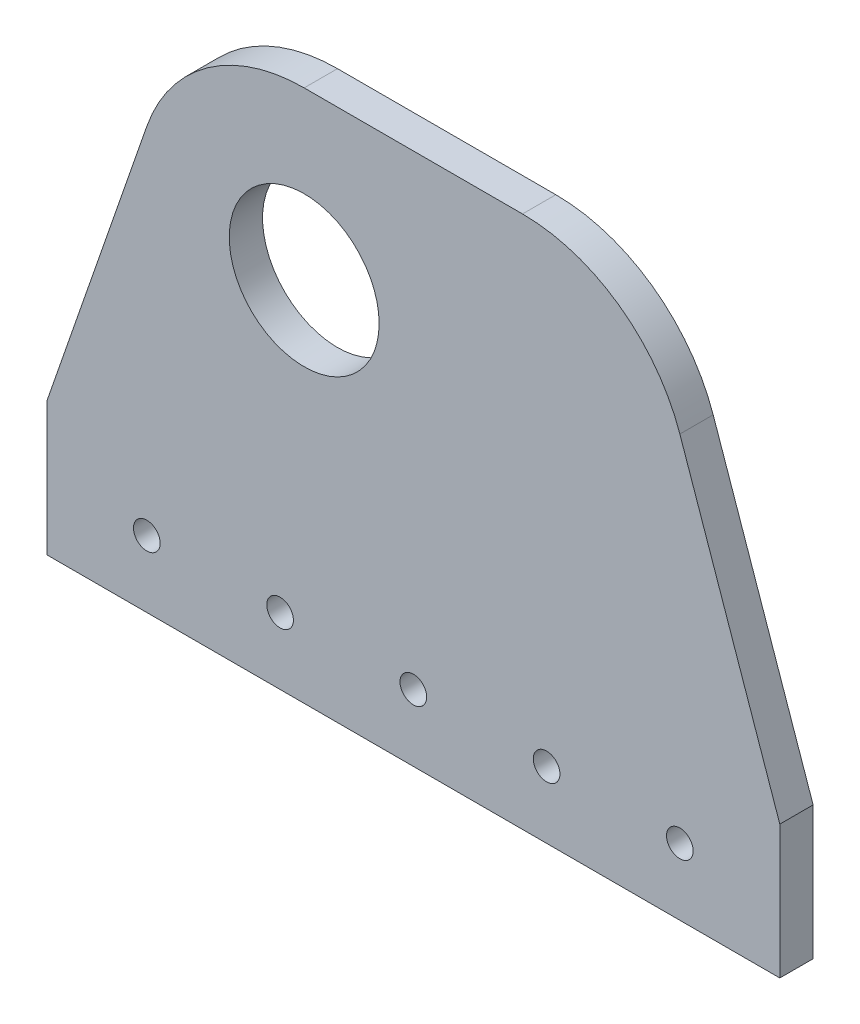
SolidWorks part; units mm, degrees
ref_plane "Front Plane" through (0, 0, 0) normal (0, 0, 1) x (1, 0, 0)
ref_plane "Top Plane" through (0, 0, 0) normal (0, 1, 0) x (1, 0, 0)
ref_plane "Right Plane" through (0, 0, 0) normal (1, 0, 0) x (0, 0, -1)
sketch "Sketch1" plane through (0, 0, 0) normal (0, 0, 1) x (1, 0, 0)
  line L1 (49.0434, 101.6) -> (90.6566, 101.6)
  line L2 (120.65, 80.2643) -> (139.7, 25.4)
  line L3 (139.7, 25.4) -> (139.7, 0)
  line L4 (139.7, 0) -> (0, 0)
  line L6 (0, 0) -> (0, 25.4)
  line L7 (0, 25.4) -> (19.05, 80.2643)
  line L8 (69.85, 0) -> (69.85, 101.6) construction
  arc A0 (49.0434, 101.6) -> (19.05, 80.2643) centre (49.0434, 69.85) ccw
  arc A1 (120.65, 80.2643) -> (90.6566, 101.6) centre (90.6566, 69.85) ccw
  circle A2 centre (49.0434, 69.85) radius 14.2875
  circle A3 centre (69.85, 12.7) radius 2.54
  circle A4 centre (95.25, 12.7) radius 2.54
  circle A5 centre (120.65, 12.7) radius 2.54
  circle A6 centre (44.45, 12.7) radius 2.54
  circle A7 centre (19.05, 12.7) radius 2.54
  point P11 (113.2418, 101.6)
  dimension "D4" = 31.75
  dimension "D5" = 31.75
  dimension "D6" = 28.575
  dimension "D3" = 5.08
  dimension "D1" = 139.7
  dimension "D2" = 19.05
  dimension "D7" = 25.4
  dimension "D8" = 101.6
  dimension "D9" = 25.4
  dimension "D10" = 12.7
  dimension "D11" = 3
  dimension "D12" = 3
extrude "Boss-Extrude1" add sketch "Sketch1" along normal blind 6.35
